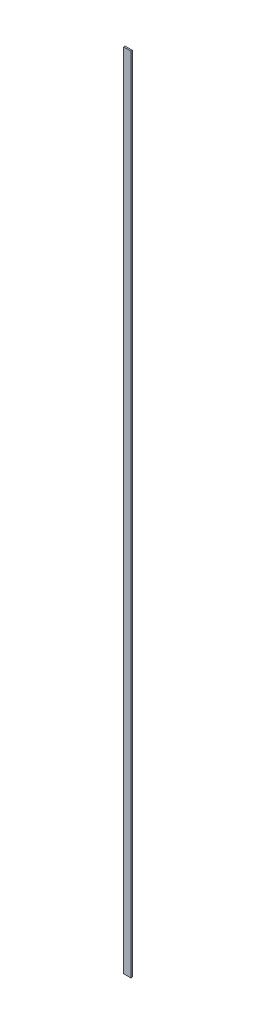
SolidWorks part; units mm, degrees
ref_plane "Спереди" through (0, 0, 0) normal (0, 0, 1) x (1, 0, 0)
ref_plane "Сверху" through (0, 0, 0) normal (0, 1, 0) x (1, 0, 0)
ref_plane "Справа" through (0, 0, 0) normal (1, 0, 0) x (0, 0, -1)
sketch "Эскиз1" plane through (0, 0, 0) normal (0, 1, 0) x (1, 0, 0)
  line L1 (25, -5) -> (-25, -5)
  line L2 (25, -5) -> (25, 5)
  line L3 (25, 5) -> (-25, 5)
  line L4 (-25, -5) -> (-25, 5)
  line L5 (25, -5) -> (-25, 5) construction
  line L6 (25, 5) -> (-25, -5) construction
  point P0 (0, 0)
  dimension "D1" = 10
  dimension "D2" = 50
extrude "Бобышка-Вытянуть1" add sketch "Эскиз1" along normal blind 5500 contours L1 L4 L3 L2
